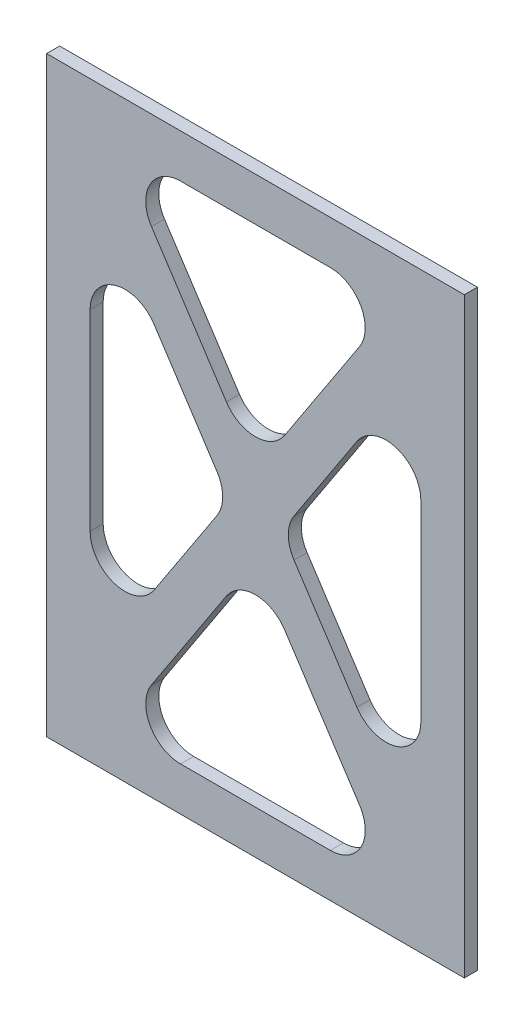
SolidWorks part; units mm, degrees
ref_plane "Plano frontal" through (0, 0, 0) normal (0, 0, 1) x (1, 0, 0)
ref_plane "Plano superior" through (0, 0, 0) normal (0, 1, 0) x (1, 0, 0)
ref_plane "Plano direito" through (0, 0, 0) normal (1, 0, 0) x (0, 0, -1)
sketch "Esboço1" plane through (0, 0, 0) normal (0, 0, 1) x (1, 0, 0)
  line L1 (-48, -68) -> (48, -68)
  line L2 (-48, -68) -> (-48, 68)
  line L3 (-48, 68) -> (48, 68)
  line L4 (48, -68) -> (48, 68)
  line L5 (-48, -68) -> (48, 68) construction
  line L6 (-48, 68) -> (48, -68) construction
  point P0 (0, 0)
  dimension "D1" = 96
  dimension "D2" = 136
extrude "Ressalto-extrusão1" add sketch "Esboço1" along normal blind 3
sketch "Esboço2" plane through (0, 0, 3) normal (0, 0, 1) x (1, 0, 0)
  line L4 (38, 58) -> (-38, -58)
  line L5 (-38, 58) -> (38, -58)
  line L6 (-42.1823, 55.2599) -> (33.8177, -60.7401)
  line L7 (33.8177, 60.7401) -> (-42.1823, -55.2599)
  line L8 (38, -58) -> (38, 58)
  line L9 (38, 58) -> (-38, 58)
  line L10 (-38, 58) -> (-38, -58)
  line L11 (-38, -58) -> (38, -58)
  line L12 (38, -58) -> (38, 58)
  line L13 (38, 58) -> (-38, 58)
  line L14 (-38, 58) -> (-38, -58)
  line L15 (-38, -58) -> (38, -58)
  line L16 (-33.8177, 60.7401) -> (42.1823, -55.2599)
  line L17 (42.1823, 55.2599) -> (-33.8177, -60.7401)
  dimension "D2" = 5
  dimension "D1" = 10
  dimension "D3" = 5
extrude "Corte-extrusão1" cut sketch "Esboço2" against normal blind 10 contours L6 L14 L7 | L13 L16 L7 | L12 L17 L16 | L6 L17 L15
fillet "Filete1" radius 8 12 edges at (38, -48.8763, 1.5) (32.0224, -58, 1.5) (0, -9.1237, 1.5) (-32.0224, -58, 1.5) (-38, -48.8763, 1.5) (-38, 48.8763, 1.5) (5.9776, 0, 1.5) (-5.9776, 0, 1.5) (0, 9.1237, 1.5) (38, 48.8763, 1.5) (32.0224, 58, 1.5) (-32.0224, 58, 1.5)
